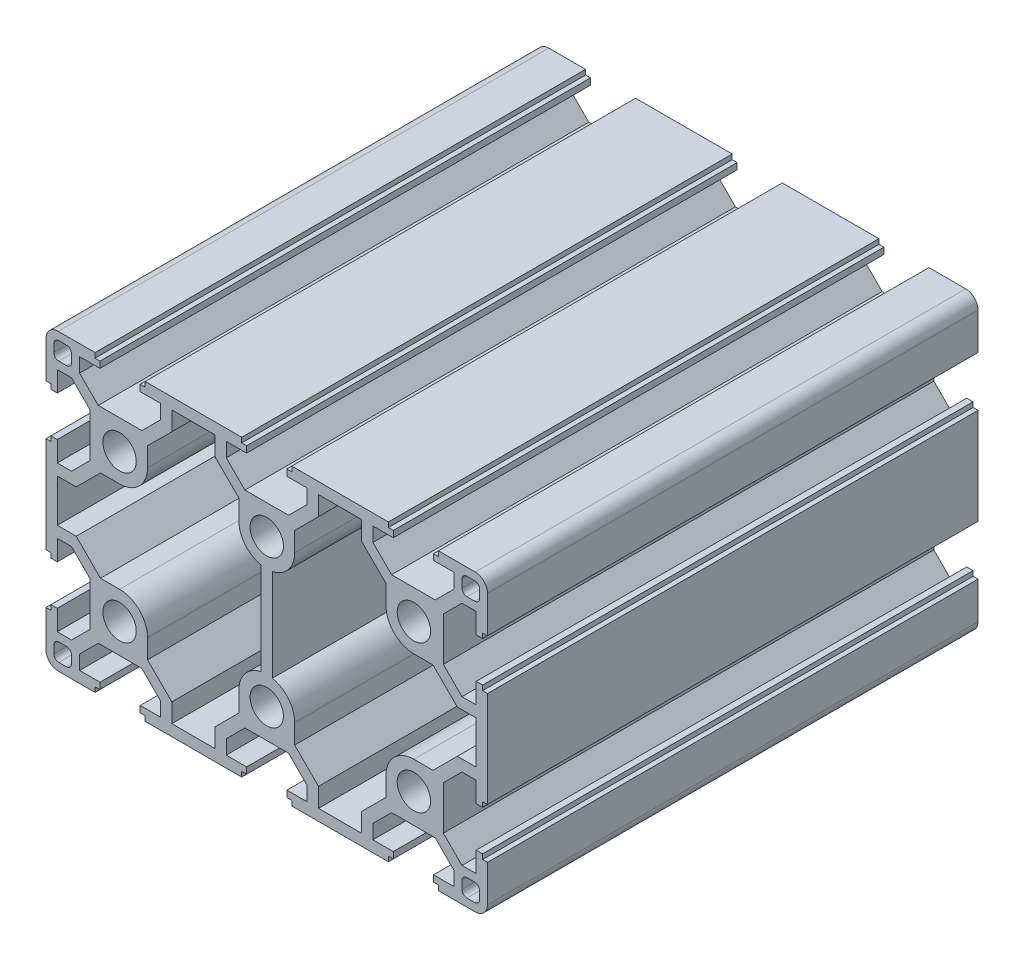
SolidWorks part; units mm, degrees
ref_plane "前视基准面" through (0, 0, 0) normal (0, 0, 1) x (1, 0, 0)
ref_plane "上视基准面" through (0, 0, 0) normal (0, 1, 0) x (1, 0, 0)
ref_plane "右视基准面" through (0, 0, 0) normal (1, 0, 0) x (0, 0, -1)
sketch "草图1" plane through (0, 0, 0) normal (0, 0, 1) x (1, 0, 0)
  line B0 (-13.4, -42.4) -> (-13.4, -40.8)
  line B1 (-12.4, -39.8) -> (-10.8, -39.8)
  line B2 (-9.8, -40.8) -> (-9.8, -42.4)
  line B3 (-10.8, -43.4) -> (-12.4, -43.4)
  line B4 (-12.4, 13.4) -> (-10.8, 13.4)
  line B5 (-9.8, 12.4) -> (-9.8, 10.8)
  line B6 (-10.8, 9.8) -> (-12.4, 9.8)
  line B7 (-13.4, 10.8) -> (-13.4, 12.4)
  line B8 (24.3, 3.9973) -> (24.3, 0)
  line B9 (28.85, -5.5828) -> (28.85, -24.4172)
  line B10 (24.3, -30) -> (24.3, -33.9973)
  line B11 (24.3, -33.9973) -> (19.45, -38.8473)
  line B12 (19.45, -38.8473) -> (19.45, -42.7)
  line B13 (19.45, -42.7) -> (10.65, -42.7)
  line B14 (10.65, -42.7) -> (10.65, -38.8473)
  line B15 (10.65, -38.8473) -> (5.7, -33.8973)
  line B16 (5.7, -33.8973) -> (5.7, -30)
  line B17 (0, -24.3) -> (-3.8973, -24.3)
  line B18 (-3.8973, -24.3) -> (-8.8473, -19.35)
  line B19 (-8.8473, -19.35) -> (-12.7, -19.35)
  line B20 (-12.7, -19.35) -> (-12.7, -10.65)
  line B21 (-12.7, -10.65) -> (-8.8473, -10.65)
  line B22 (-8.8473, -10.65) -> (-3.8973, -5.7)
  line B23 (-3.8973, -5.7) -> (0, -5.7)
  line B24 (5.7, 0) -> (5.7, 3.8973)
  line B25 (5.7, 3.8973) -> (10.65, 8.8473)
  line B26 (10.65, 8.8473) -> (10.65, 12.7)
  line B27 (10.65, 12.7) -> (19.45, 12.7)
  line B28 (19.45, 12.7) -> (19.45, 8.8473)
  line B29 (19.45, 8.8473) -> (24.3, 3.9973)
  line B30 (72.4, -43.4) -> (70.8, -43.4)
  line B31 (69.8, -42.4) -> (69.8, -40.8)
  line B32 (70.8, -39.8) -> (72.4, -39.8)
  line B33 (73.4, -40.8) -> (73.4, -42.4)
  line B34 (72.7, -10.65) -> (72.7, -19.35)
  line B35 (72.7, -19.35) -> (68.8473, -19.35)
  line B36 (68.8473, -19.35) -> (63.8973, -24.3)
  line B37 (63.8973, -24.3) -> (60, -24.3)
  line B38 (54.3, -30) -> (54.3, -33.8973)
  line B39 (54.3, -33.8973) -> (49.35, -38.8473)
  line B40 (49.35, -38.8473) -> (49.35, -42.7)
  line B41 (49.35, -42.7) -> (40.55, -42.7)
  line B42 (40.55, -42.7) -> (40.55, -38.8)
  line B43 (40.55, -38.8) -> (35.7, -33.95)
  line B44 (35.7, -33.95) -> (35.7, -30)
  line B45 (31.15, -24.4172) -> (31.15, -5.5828)
  line B46 (35.7, 0) -> (35.7, 3.95)
  line B47 (35.7, 3.95) -> (40.55, 8.8)
  line B48 (40.55, 8.8) -> (40.55, 12.7)
  line B49 (40.55, 12.7) -> (49.35, 12.7)
  line B50 (49.35, 12.7) -> (49.35, 8.8473)
  line B51 (49.35, 8.8473) -> (54.3, 3.8973)
  line B52 (54.3, 3.8973) -> (54.3, 0)
  line B53 (60, -5.7) -> (63.8973, -5.7)
  line B54 (63.8973, -5.7) -> (68.8473, -10.65)
  line B55 (68.8473, -10.65) -> (72.7, -10.65)
  line B56 (73.4, 12.4) -> (73.4, 10.8)
  line B57 (72.4, 9.8) -> (70.8, 9.8)
  line B58 (69.8, 10.8) -> (69.8, 12.4)
  line B59 (70.8, 13.4) -> (72.4, 13.4)
  line B60 (-4.35, -36) -> (4.55, -36)
  line B61 (4.55, -36) -> (8.35, -39.8)
  line B62 (8.35, -39.8) -> (8.35, -42.7)
  line B63 (8.35, -42.7) -> (4.2, -42.7)
  line B64 (4.2, -42.7) -> (4.2, -44)
  line B65 (4.2, -44) -> (5.2, -44)
  line B66 (5.2, -44) -> (5.2, -45)
  line B67 (5.2, -45) -> (24.9, -45)
  line B68 (24.9, -45) -> (24.9, -44)
  line B69 (24.9, -44) -> (25.9, -44)
  line B70 (25.9, -44) -> (25.9, -42.7)
  line B71 (25.9, -42.7) -> (21.75, -42.7)
  line B72 (21.75, -42.7) -> (21.75, -39.8)
  line B73 (21.75, -39.8) -> (25.55, -36)
  line B74 (25.55, -36) -> (34.45, -36)
  line B75 (34.45, -36) -> (38.25, -39.8)
  line B76 (38.25, -39.8) -> (38.25, -42.7)
  line B77 (38.25, -42.7) -> (34.1, -42.7)
  line B78 (34.1, -42.7) -> (34.1, -44)
  line B79 (34.1, -44) -> (35.1, -44)
  line B80 (35.1, -44) -> (35.1, -45)
  line B81 (35.1, -45) -> (54.8, -45)
  line B82 (54.8, -45) -> (54.8, -44)
  line B83 (54.8, -44) -> (55.8, -44)
  line B84 (55.8, -44) -> (55.8, -42.7)
  line B85 (55.8, -42.7) -> (51.65, -42.7)
  line B86 (51.65, -42.7) -> (51.65, -39.8)
  line B87 (51.65, -39.8) -> (55.45, -36)
  line B88 (55.45, -36) -> (64.35, -36)
  line B89 (64.35, -36) -> (68.15, -39.8)
  line B90 (68.15, -39.8) -> (68.15, -42.7)
  line B91 (68.15, -42.7) -> (64, -42.7)
  line B92 (64, -42.7) -> (64, -44)
  line B93 (64, -44) -> (65, -44)
  line B94 (65, -44) -> (65, -45)
  line B95 (65, -45) -> (72.5, -45)
  line B96 (75, -42.5) -> (75, -35)
  line B97 (75, -35) -> (74, -35)
  line B98 (74, -35) -> (74, -34)
  line B99 (74, -34) -> (72.7, -34)
  line B100 (72.7, -34) -> (72.7, -38.15)
  line B101 (72.7, -38.15) -> (69.8, -38.15)
  line B102 (69.8, -38.15) -> (66, -34.35)
  line B103 (66, -34.35) -> (66, -25.45)
  line B104 (66, -25.45) -> (69.8, -21.65)
  line B105 (69.8, -21.65) -> (72.7, -21.65)
  line B106 (72.7, -21.65) -> (72.7, -25.8)
  line B107 (72.7, -25.8) -> (74, -25.8)
  line B108 (74, -25.8) -> (74, -24.8)
  line B109 (74, -24.8) -> (75, -24.8)
  line B110 (75, -24.8) -> (75, -5.2)
  line B111 (75, -5.2) -> (74, -5.2)
  line B112 (74, -5.2) -> (74, -4.2)
  line B113 (74, -4.2) -> (72.7, -4.2)
  line B114 (72.7, -4.2) -> (72.7, -8.35)
  line B115 (72.7, -8.35) -> (69.8, -8.35)
  line B116 (69.8, -8.35) -> (66, -4.55)
  line B117 (66, -4.55) -> (66, 4.35)
  line B118 (66, 4.35) -> (69.8, 8.15)
  line B119 (69.8, 8.15) -> (72.7, 8.15)
  line B120 (72.7, 8.15) -> (72.7, 4)
  line B121 (72.7, 4) -> (74, 4)
  line B122 (74, 4) -> (74, 5)
  line B123 (74, 5) -> (75, 5)
  line B124 (75, 5) -> (75, 12.5)
  line B125 (72.5, 15) -> (65, 15)
  line B126 (65, 15) -> (65, 14)
  line B127 (65, 14) -> (64, 14)
  line B128 (64, 14) -> (64, 12.8)
  line B129 (64, 12.8) -> (68.15, 12.8)
  line B130 (68.15, 12.8) -> (68.15, 9.8)
  line B131 (68.15, 9.8) -> (64.35, 6)
  line B132 (64.35, 6) -> (55.45, 6)
  line B133 (55.45, 6) -> (51.65, 9.8)
  line B134 (51.65, 9.8) -> (51.65, 12.7)
  line B135 (51.65, 12.7) -> (55.8, 12.7)
  line B136 (55.8, 12.7) -> (55.8, 14)
  line B137 (55.8, 14) -> (54.8, 14)
  line B138 (54.8, 14) -> (54.8, 15)
  line B139 (54.8, 15) -> (35.1, 15)
  line B140 (35.1, 15) -> (35.1, 14)
  line B141 (35.1, 14) -> (34.1, 14)
  line B142 (34.1, 14) -> (34.1, 12.7)
  line B143 (34.1, 12.7) -> (38.25, 12.7)
  line B144 (38.25, 12.7) -> (38.25, 9.8)
  line B145 (38.25, 9.8) -> (34.45, 6)
  line B146 (34.45, 6) -> (25.55, 6)
  line B147 (25.55, 6) -> (21.75, 9.8)
  line B148 (21.75, 9.8) -> (21.75, 12.7)
  line B149 (21.75, 12.7) -> (25.9, 12.7)
  line B150 (25.9, 12.7) -> (25.9, 14)
  line B151 (25.9, 14) -> (24.9, 14)
  line B152 (24.9, 14) -> (24.9, 15)
  line B153 (24.9, 15) -> (5.2, 15)
  line B154 (5.2, 15) -> (5.2, 14)
  line B155 (5.2, 14) -> (4.2, 14)
  line B156 (4.2, 14) -> (4.2, 12.7)
  line B157 (4.2, 12.7) -> (8.35, 12.7)
  line B158 (8.35, 12.7) -> (8.35, 9.8)
  line B159 (8.35, 9.8) -> (4.55, 6)
  line B160 (4.55, 6) -> (-4.35, 6)
  line B161 (-4.35, 6) -> (-8.15, 9.8)
  line B162 (-8.15, 9.8) -> (-8.15, 12.7)
  line B163 (-8.15, 12.7) -> (-4, 12.7)
  line B164 (-4, 12.7) -> (-4, 14)
  line B165 (-4, 14) -> (-5, 14)
  line B166 (-5, 14) -> (-5, 15)
  line B167 (-5, 15) -> (-12.5, 15)
  line B168 (-15, 12.5) -> (-15, 5)
  line B169 (-15, 5) -> (-14, 5)
  line B170 (-14, 5) -> (-14, 4)
  line B171 (-14, 4) -> (-12.7, 4)
  line B172 (-12.7, 4) -> (-12.7, 8.15)
  line B173 (-12.7, 8.15) -> (-9.8, 8.15)
  line B174 (-9.8, 8.15) -> (-6, 4.35)
  line B175 (-6, 4.35) -> (-6, -4.55)
  line B176 (-6, -4.55) -> (-9.8, -8.35)
  line B177 (-9.8, -8.35) -> (-12.7, -8.35)
  line B178 (-12.7, -8.35) -> (-12.7, -4.2)
  line B179 (-12.7, -4.2) -> (-14, -4.2)
  line B180 (-14, -4.2) -> (-14, -5.2)
  line B181 (-14, -5.2) -> (-15, -5.2)
  line B182 (-15, -5.2) -> (-15, -24.8)
  line B183 (-15, -24.8) -> (-14, -24.8)
  line B184 (-14, -24.8) -> (-14, -25.8)
  line B185 (-14, -25.8) -> (-12.7, -25.8)
  line B186 (-12.7, -25.8) -> (-12.7, -21.65)
  line B187 (-12.7, -21.65) -> (-9.8, -21.65)
  line B188 (-9.8, -21.65) -> (-6, -25.45)
  line B189 (-6, -25.45) -> (-6, -34.35)
  line B190 (-6, -34.35) -> (-9.8, -38.15)
  line B191 (-9.8, -38.15) -> (-12.7, -38.15)
  line B192 (-12.7, -38.15) -> (-12.7, -34)
  line B193 (-12.7, -34) -> (-14, -34)
  line B194 (-14, -34) -> (-14, -35)
  line B195 (-14, -35) -> (-15, -35)
  line B196 (-15, -35) -> (-15, -42.5)
  line B197 (-12.5, -45) -> (-5, -45)
  line B198 (-5, -45) -> (-5, -44)
  line B199 (-5, -44) -> (-4, -44)
  line B200 (-4, -44) -> (-4, -42.7)
  line B201 (-4, -42.7) -> (-8.15, -42.7)
  line B202 (-8.15, -42.7) -> (-8.15, -39.8)
  line B203 (-8.15, -39.8) -> (-4.35, -36)
  arc B204 (-13.4, -42.4) -> (-12.4, -43.4) centre (-12.4, -42.4) ccw
  arc B205 (-12.4, -39.8) -> (-13.4, -40.8) centre (-12.4, -40.8) ccw
  arc B206 (-9.8, -40.8) -> (-10.8, -39.8) centre (-10.8, -40.8) ccw
  arc B207 (-10.8, -43.4) -> (-9.8, -42.4) centre (-10.8, -42.4) ccw
  arc B208 (-12.4, 13.4) -> (-13.4, 12.4) centre (-12.4, 12.4) ccw
  arc B209 (-9.8, 12.4) -> (-10.8, 13.4) centre (-10.8, 12.4) ccw
  arc B210 (-10.8, 9.8) -> (-9.8, 10.8) centre (-10.8, 10.8) ccw
  arc B211 (-13.4, 10.8) -> (-12.4, 9.8) centre (-12.4, 10.8) ccw
  circle B212 centre (0, -30) radius 3.4
  circle B213 centre (0, 0) radius 3.4
  arc B214 (24.3, 0) -> (28.85, -5.5828) centre (30, 0) ccw
  arc B215 (28.85, -24.4172) -> (24.3, -30) centre (30, -30) ccw
  arc B216 (5.7, -30) -> (0, -24.3) centre (0, -30) ccw
  arc B217 (0, -5.7) -> (5.7, 0) centre (0, 0) ccw
  circle B218 centre (30, 0) radius 3.4
  circle B219 centre (30, -30) radius 3.4
  arc B220 (72.4, -43.4) -> (73.4, -42.4) centre (72.4, -42.4) ccw
  arc B221 (69.8, -42.4) -> (70.8, -43.4) centre (70.8, -42.4) ccw
  arc B222 (70.8, -39.8) -> (69.8, -40.8) centre (70.8, -40.8) ccw
  arc B223 (73.4, -40.8) -> (72.4, -39.8) centre (72.4, -40.8) ccw
  circle B224 centre (60, -30) radius 3.4
  arc B225 (60, -24.3) -> (54.3, -30) centre (60, -30) ccw
  arc B226 (35.7, -30) -> (31.15, -24.4172) centre (30, -30) ccw
  arc B227 (31.15, -5.5828) -> (35.7, 0) centre (30, 0) ccw
  arc B228 (54.3, 0) -> (60, -5.7) centre (60, 0) ccw
  circle B229 centre (60, 0) radius 3.4
  arc B230 (73.4, 12.4) -> (72.4, 13.4) centre (72.4, 12.4) ccw
  arc B231 (72.4, 9.8) -> (73.4, 10.8) centre (72.4, 10.8) ccw
  arc B232 (69.8, 10.8) -> (70.8, 9.8) centre (70.8, 10.8) ccw
  arc B233 (70.8, 13.4) -> (69.8, 12.4) centre (70.8, 12.4) ccw
  arc B234 (72.5, -45) -> (75, -42.5) centre (72.5, -42.5) ccw
  arc B235 (75, 12.5) -> (72.5, 15) centre (72.5, 12.5) ccw
  arc B236 (-12.5, 15) -> (-15, 12.5) centre (-12.5, 12.5) ccw
  arc B237 (-15, -42.5) -> (-12.5, -45) centre (-12.5, -42.5) ccw
sketch_block_instance "A$C2D6D5E0B-1"
sketch_block "A$C2D6D5E0B"
extrude "凸台-拉伸1" add sketch "草图1" along normal blind 100
